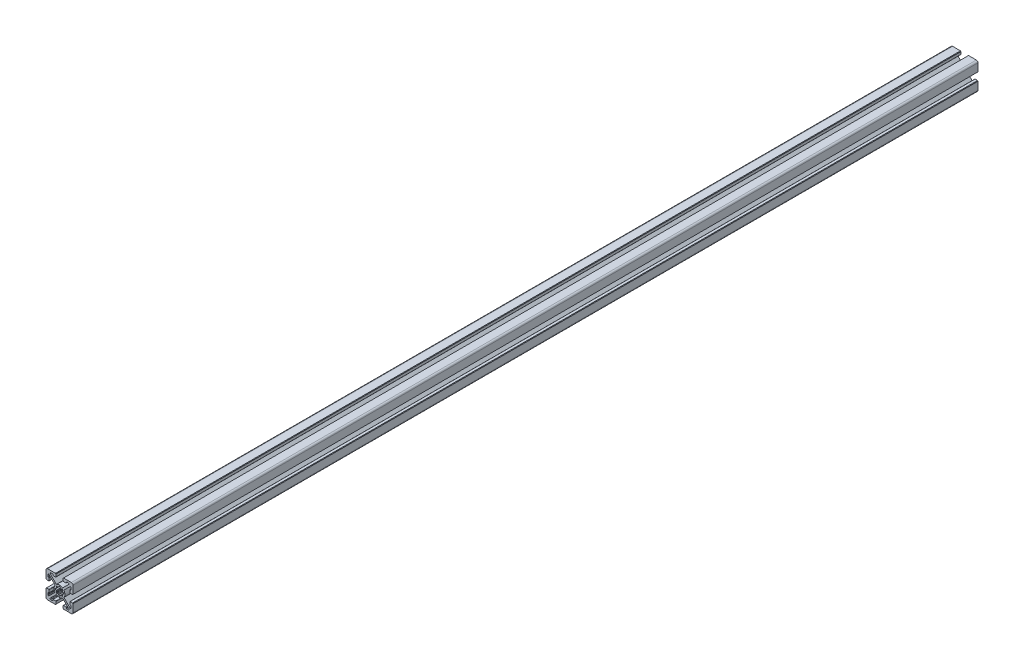
SolidWorks part; units mm, degrees
ref_plane "Alzado" through (0, 0, 0) normal (0, 0, 1) x (1, 0, 0)
ref_plane "Planta" through (0, 0, 0) normal (0, 1, 0) x (1, 0, 0)
ref_plane "Vista lateral" through (0, 0, 0) normal (1, 0, 0) x (0, 0, -1)
sketch "Croquis1" plane through (0, 0, 0) normal (0, 0, 1) x (1, 0, 0)
  line L0 (15, 15) -> (-15, -15) construction
  line L1 (4, 15) -> (15, 15)
  line L2 (-15, -13.9276) -> (-15, -15)
  line L3 (0, 0) -> (21.2084, 0) construction
  line L4 (15, 15) -> (15, 4)
  line L5 (-15, -15) -> (-15, -13.9276) construction
  line L6 (0, 0) -> (0, 3.75) construction
  line L7 (-1, 3.6142) -> (0, 5.25)
  line L8 (0, 5.25) -> (1, 3.6142)
  line L9 (0, 5.25) -> (0, 8.6463) construction
  line L10 (0, 5.25) -> (0, 3.75) construction
  line L11 (3.7123, 3.7123) -> (3.2627, 1.8485)
  line L12 (1.8485, 3.2627) -> (3.7123, 3.7123)
  line L13 (5.25, 0) -> (3.6142, -1)
  line L14 (3.6142, 1) -> (5.25, 0)
  line L15 (3.7123, -3.7123) -> (1.8485, -3.2627)
  line L16 (3.2627, -1.8485) -> (3.7123, -3.7123)
  line L17 (0, -5.25) -> (-1, -3.6142)
  line L18 (1, -3.6142) -> (0, -5.25)
  line L19 (-3.7123, -3.7123) -> (-3.2627, -1.8485)
  line L20 (-1.8485, -3.2627) -> (-3.7123, -3.7123)
  line L21 (-5.25, 0) -> (-3.6142, 1)
  line L22 (-3.6142, -1) -> (-5.25, 0)
  line L23 (-3.7123, 3.7123) -> (-1.8485, 3.2627)
  line L24 (-3.2627, 1.8485) -> (-3.7123, 3.7123)
  line L25 (10.7574, 12.1716) -> (3.4762, 4.8904)
  line L26 (4, 11.5) -> (4, 15)
  line L27 (12.1716, 10.7574) -> (4.8904, 3.4762)
  line L28 (9.9289, 13) -> (7.5, 13)
  line L29 (11.5, 4) -> (15, 4)
  line L30 (13, 9.9289) -> (13, 7.5)
  line L31 (13.5858, 15) -> (15, 13.5858) construction
  line L32 (9.9289, 13) -> (10.7574, 12.1716)
  line L33 (12.1716, 10.7574) -> (13, 9.9289)
  line L34 (13.5858, -15) -> (15, -13.5858) construction
  line L35 (4, 11.5) -> (7.5, 11.5)
  line L36 (7.5, 11.5) -> (7.5, 13)
  line L37 (11.5, 7.5) -> (13, 7.5)
  line L38 (11.5, 4) -> (11.5, 7.5)
  line L39 (15, -15) -> (-15, 15) construction
  line L40 (11.5, -4) -> (11.5, -7.5)
  line L41 (11.5, -7.5) -> (13, -7.5)
  line L42 (12.1716, -10.7574) -> (13, -9.9289)
  line L43 (13, -9.9289) -> (13, -7.5)
  line L44 (11.5, -4) -> (15, -4)
  line L45 (12.1716, -10.7574) -> (4.8904, -3.4762)
  line L46 (15, -15) -> (15, -4)
  line L47 (4, -15) -> (15, -15)
  line L48 (4, -11.5) -> (4, -15)
  line L49 (4, -11.5) -> (7.5, -11.5)
  line L50 (7.5, -11.5) -> (7.5, -13)
  line L51 (9.9289, -13) -> (7.5, -13)
  line L52 (9.9289, -13) -> (10.7574, -12.1716)
  line L53 (10.7574, -12.1716) -> (3.4762, -4.8904)
  line L54 (-7.5, -11.5) -> (-7.5, -13)
  line L55 (-4, -11.5) -> (-7.5, -11.5)
  line L56 (-4, -11.5) -> (-4, -15)
  line L57 (-15, -15) -> (15, 15) construction
  line L58 (-13.5858, -15) -> (-15, -13.5858) construction
  line L59 (-10.7574, -12.1716) -> (-3.4762, -4.8904)
  line L60 (-9.9289, -13) -> (-10.7574, -12.1716)
  line L61 (-9.9289, -13) -> (-7.5, -13)
  line L62 (-4, -15) -> (-15, -15)
  line L63 (-15, -15) -> (-15, -4)
  line L64 (-12.1716, -10.7574) -> (-4.8904, -3.4762)
  line L65 (-11.5, -4) -> (-15, -4)
  line L66 (-13, -9.9289) -> (-13, -7.5)
  line L67 (-12.1716, -10.7574) -> (-13, -9.9289)
  line L68 (-11.5, -7.5) -> (-13, -7.5)
  line L69 (-11.5, -4) -> (-11.5, -7.5)
  line L70 (-15, 15) -> (15, -15) construction
  line L71 (-11.5, 4) -> (-11.5, 7.5)
  line L72 (-11.5, 7.5) -> (-13, 7.5)
  line L73 (-12.1716, 10.7574) -> (-13, 9.9289)
  line L74 (-13, 9.9289) -> (-13, 7.5)
  line L75 (-11.5, 4) -> (-15, 4)
  line L76 (-12.1716, 10.7574) -> (-4.8904, 3.4762)
  line L77 (-10.7574, 12.1716) -> (-3.4762, 4.8904)
  line L78 (-15, 15) -> (-15, 4)
  line L79 (-13.5858, 15) -> (-15, 13.5858) construction
  line L80 (-7.5, 11.5) -> (-7.5, 13)
  line L81 (-4, 11.5) -> (-7.5, 11.5)
  line L82 (-9.9289, 13) -> (-10.7574, 12.1716)
  line L83 (-9.9289, 13) -> (-7.5, 13)
  line L84 (-4, 11.5) -> (-4, 15)
  line L85 (-4, 15) -> (-15, 15)
  arc A0 (3.4762, 4.8904) -> (-3.4762, 4.8904) centre (0, 0) ccw
  arc A1 (-1, 3.6142) -> (-1.8485, 3.2627) centre (0, 0) ccw
  arc A2 (-3.2627, 1.8485) -> (-3.6142, 1) centre (0, 0) ccw
  arc A3 (-3.6142, -1) -> (-3.2627, -1.8485) centre (0, 0) ccw
  arc A4 (-1.8485, -3.2627) -> (-1, -3.6142) centre (0, 0) ccw
  arc A5 (1, -3.6142) -> (1.8485, -3.2627) centre (0, 0) ccw
  arc A6 (3.2627, -1.8485) -> (3.6142, -1) centre (0, 0) ccw
  arc A7 (3.6142, 1) -> (3.2627, 1.8485) centre (0, 0) ccw
  arc A8 (1.8485, 3.2627) -> (1, 3.6142) centre (0, 0) ccw
  arc A9 (-3.4762, -4.8904) -> (3.4762, -4.8904) centre (0, 0) ccw
  arc A10 (4.8904, -3.4762) -> (4.8904, 3.4762) centre (0, 0) ccw
  arc A11 (-4.8904, 3.4762) -> (-4.8904, -3.4762) centre (0, 0) ccw
  dimension "D3" = 12
  dimension "D4" = 7.5
  dimension "D5" = 1
  dimension "D6" = 1
  dimension "D7" = 1.5
  dimension "D9" = 1
  dimension "D10" = 1
  dimension "D11" = 11
  dimension "D14" = 2
  dimension "D16" = 4
  dimension "D17" = 3.5
  dimension "D8" = 8
extrude "Saliente-Extruir1" add sketch "Croquis1" along normal blind 1005 contours L76 A11 L64 L67 L66 L68 L69 L65 L63 L2 L62 L56 L55 L54 L61 L60 L59 A9 L53 L52 L51 L50 L49 L48 L47 L46 L44 L40 L41 L43 L42 L45 A10 L27 L33 L30 L37 L38 L29 L4 L1 L26 L35 L36 L28 L32 L25 A0 L77 L82 L83
fillet "Redondeo1" radius 0.3 63 edges at (3.2627, 1.8485, 502.5) (3.6142, 1, 502.5) (5.25, 0, 502.5) (3.6142, -1, 502.5) (3.2627, -1.8485, 502.5) (3.7123, -3.7123, 502.5) (1.8485, -3.2627, 502.5) (1, -3.6142, 502.5) (0, -5.25, 502.5) (-1, -3.6142, 502.5) (-1.8485, -3.2627, 502.5) (-3.7123, -3.7123, 502.5) (-3.2627, -1.8485, 502.5) (-3.6142, -1, 502.5) (-5.25, 0, 502.5) (-3.6142, 1, 502.5) (-3.2627, 1.8485, 502.5) (-3.7123, 3.7123, 502.5) (-1.8485, 3.2627, 502.5) (-1, 3.6142, 502.5) (0, 5.25, 502.5) (1, 3.6142, 502.5) (1.8485, 3.2627, 502.5) (3.7123, 3.7123, 502.5) (-7.5, -11.5, 502.5) (-7.5, -13, 502.5) (-9.9289, -13, 502.5) (-10.7574, -12.1716, 502.5) (-12.1716, -10.7574, 502.5) (-13, -9.9289, 502.5) (-11.5, -7.5, 502.5) (11.5, -7.5, 502.5) (13, -7.5, 502.5) (13, -9.9289, 502.5) (10.7574, -12.1716, 502.5) (12.1716, -10.7574, 502.5) (9.9289, -13, 502.5) (7.5, -13, 502.5) (7.5, -11.5, 502.5) (-11.5, 7.5, 502.5) (-7.5, 11.5, 502.5) (11.5, 7.5, 502.5) (13, 7.5, 502.5) (12.1716, 10.7574, 502.5) (13, 9.9289, 502.5) (10.7574, 12.1716, 502.5) (9.9289, 13, 502.5) (7.5, 11.5, 502.5) (7.5, 13, 502.5) (-7.5, 13, 502.5) (-13, 7.5, 502.5) (-9.9289, 13, 502.5) (-10.7574, 12.1716, 502.5) (-13, 9.9289, 502.5) (-12.1716, 10.7574, 502.5) (-11.5, 4, 502.5) (-11.5, -4, 502.5) (-4, -11.5, 502.5) (4, -11.5, 502.5) (11.5, -4, 502.5) (11.5, 4, 502.5) (4, 11.5, 502.5) (-4, 11.5, 502.5)
fillet "Redondeo2" radius 1.8 4 edges at (-15, 15, 502.5) (-15, -15, 502.5) (15, -15, 502.5) (15, 15, 502.5)
chamfer "Chaflán1" distance 0.5 angle 45 8 edges at (-15, 4, 502.5) (-15, -4, 502.5) (-4, -15, 502.5) (4, -15, 502.5) (15, -4, 502.5) (15, 4, 502.5) (4, 15, 502.5) (-4, 15, 502.5)
sketch "Croquis2" plane through (0, 0, 1005) normal (0, 0, 1) x (1, 0, 0)
  line L0 (-7.2, 9.4571) -> (-8.7429, 11)
  line L1 (4.2429, 6.5) -> (7.2, 9.4571)
  line L2 (4.5, 15) -> (13.2, 15) construction
  line L3 (7.2, 9.4571) -> (8.7429, 11)
  line L4 (7.2, 11) -> (8.7429, 11)
  line L5 (-7.2, 11) -> (-8.7429, 11)
  line L6 (-7.2, 11) -> (7.2, 11)
  line L9 (-4.2429, 6.5) -> (4.2429, 6.5)
  line L12 (-7.2, 9.4571) -> (-4.2429, 6.5)
  dimension "D1" = 17.4858
  dimension "D2" = 8.4858
  dimension "D3" = 4.5
  dimension "D4" = 8.5
